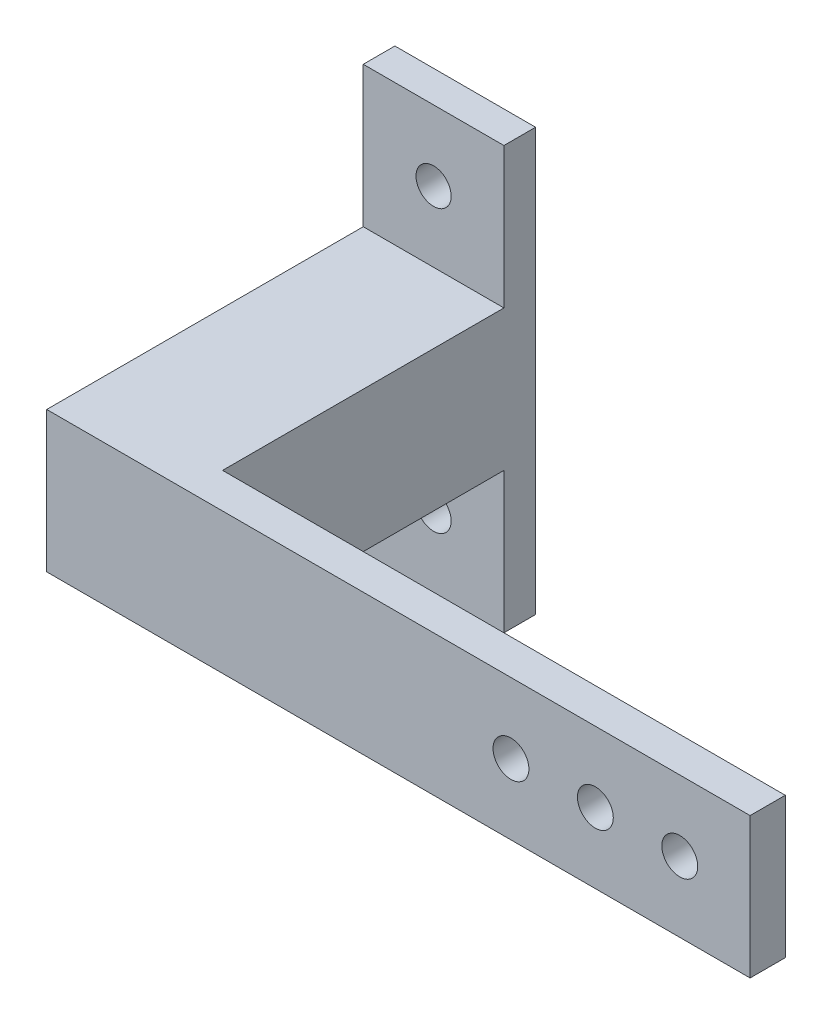
SolidWorks part; units mm, degrees
ref_plane "前视基准面" through (0, 0, 0) normal (0, 0, 1) x (1, 0, 0)
ref_plane "上视基准面" through (0, 0, 0) normal (0, 1, 0) x (1, 0, 0)
ref_plane "右视基准面" through (0, 0, 0) normal (1, 0, 0) x (0, 0, -1)
sketch "草图1" plane through (0, 0, 0) normal (0, 0, 1) x (1, 0, 0)
  line L1 (10, -30) -> (-10, -30)
  line L2 (10, -30) -> (10, 30)
  line L3 (10, 30) -> (-10, 30)
  line L4 (-10, -30) -> (-10, 30)
  line L5 (10, -30) -> (-10, 30) construction
  line L6 (10, 30) -> (-10, -30) construction
  point P0 (0, 0)
  dimension "D1" = 20
  dimension "D2" = 60
extrude "凸台-拉伸1" add sketch "草图1" along normal blind 4.5
sketch "草图2" plane through (0, 0, 4.5) normal (0, 0, 1) x (1, 0, 0)
  line L0 (-10, 30) -> (-10, -30) construction
  line L1 (10, -10) -> (-10, -10)
  line L2 (10, -10) -> (10, 10)
  line L3 (10, 10) -> (-10, 10)
  line L4 (-10, -10) -> (-10, 10)
  line L5 (10, -10) -> (-10, 10) construction
  line L6 (10, 10) -> (-10, -10) construction
  point P0 (0, 0)
  dimension "D1" = 20
extrude "凸台-拉伸2" add sketch "草图2" along normal blind 40
sketch "草图3" plane through (0, 0, 44.5) normal (0, 0, 1) x (1, 0, 0)
  line L1 (-10, -10) -> (90, -10)
  line L2 (-10, -10) -> (-10, 10)
  line L3 (-10, 10) -> (90, 10)
  line L4 (90, -10) -> (90, 10)
  dimension "D1" = 20
  dimension "D2" = 100
extrude "凸台-拉伸3" add sketch "草图3" along normal blind 5
sketch "草图5" plane through (0, 0, 4.5) normal (0, 0, 1) x (1, 0, 0)
  line L0 (-10, -10) -> (90, -10) construction
  line L1 (10, 10) -> (-10, 10) construction
  circle A0 centre (0, 20) radius 2.5
  circle A1 centre (0, -20) radius 2.5
  dimension "D1" = 10
  dimension "D2" = 10
  dimension "D3" = 5
  dimension "D4" = 5
extrude "切除-拉伸2" cut sketch "草图5" against normal blind 5
sketch "草图6" plane through (0, 0, 49.5) normal (0, 0, 1) x (1, 0, 0)
  line L0 (90, -10) -> (90, 10) construction
  circle A0 centre (80, 0) radius 2.55
  circle A1 centre (68, 0) radius 2.55
  circle A2 centre (56, 0) radius 2.55
  dimension "D1" = 10
  dimension "D2" = 5.1
  dimension "D3" = 3
extrude "切除-拉伸3" cut sketch "草图6" against normal blind 10
